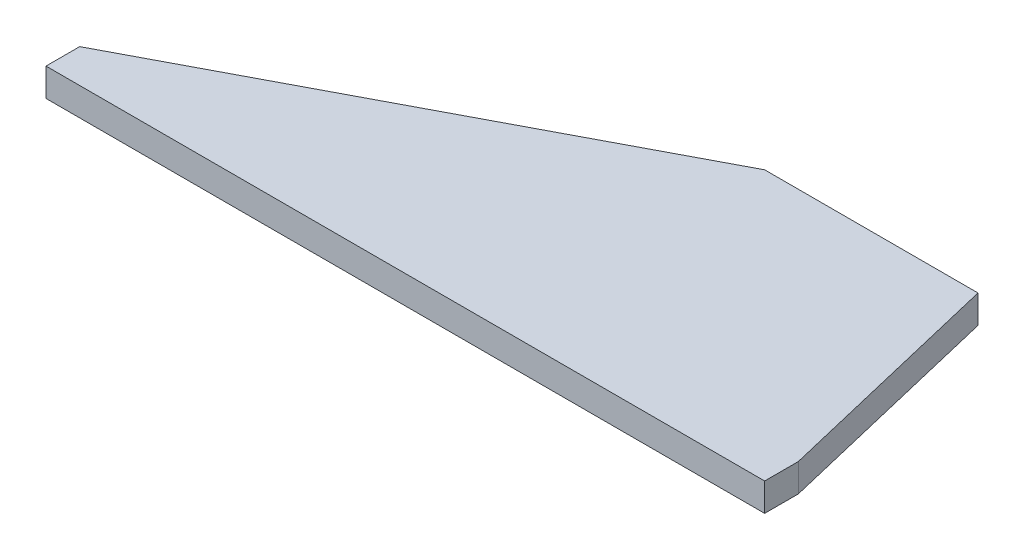
SolidWorks part; units mm, degrees
ref_plane "Front Plane" through (0, 0, 0) normal (0, 0, 1) x (1, 0, 0)
ref_plane "Top Plane" through (0, 0, 0) normal (0, 1, 0) x (1, 0, 0)
ref_plane "Right Plane" through (0, 0, 0) normal (1, 0, 0) x (0, 0, -1)
sketch "Sketch1" plane through (0, 0, 0) normal (0, 1, 0) x (1, 0, 0)
  line L0 (0, 0) -> (101.6, 53.34)
  line L1 (0, -7.62) -> (162.56, -7.62)
  line L2 (0, -7.62) -> (0, 0)
  line L4 (162.56, -7.62) -> (162.56, 0)
  line L5 (101.6, 53.34) -> (149.86, 53.34)
  line L6 (149.86, 53.34) -> (162.56, 0)
  point P5 (5.9506, -54.1024)
  point P8 (0, 0)
  point P10 (0, 0)
  point P11 (0, 0)
  point P12 (70.6894, 42.4463)
  point P13 (118.5026, 43.9405)
  dimension "D1" = 162.56
  dimension "D2" = 101.6
  dimension "D3" = 53.34
  dimension "D4" = 149.86
  dimension "D5" = 7.62
extrude "Boss-Extrude1" add sketch "Sketch1" along normal blind 6.35
ref_plane "midplane" through (0, 3.175, 0) normal (0, 1, 0) x (1, 0, 0)
ref_plane "back plane" through (165.1, 0, 0) normal (1, 0, 0) x (0, 0, -1)
